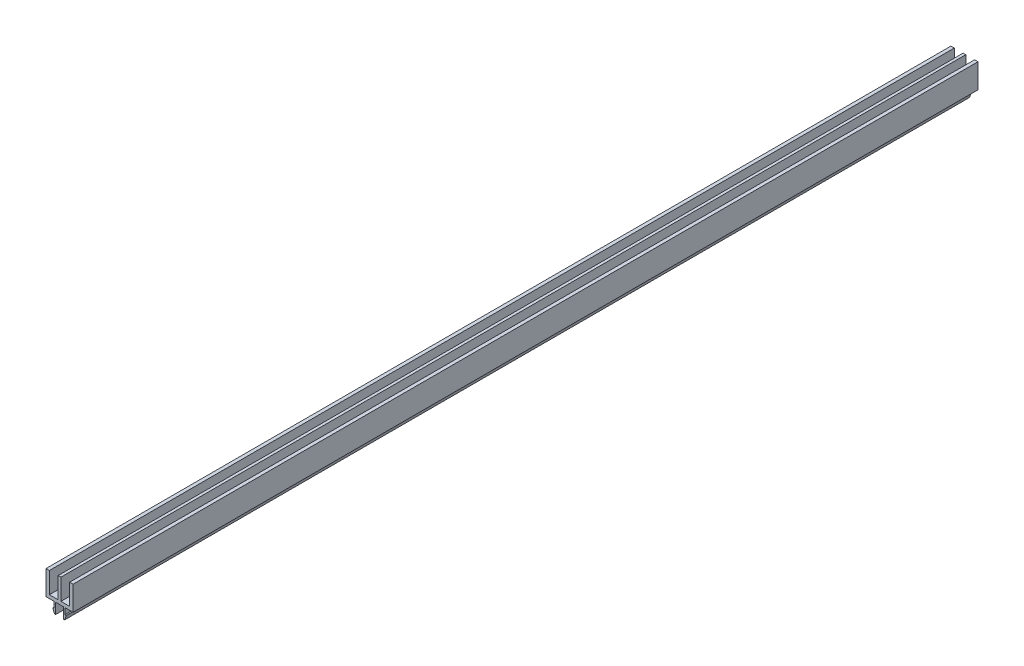
SolidWorks part; units mm, degrees
ref_plane "Plan de face" through (0, 0, 0) normal (0, 0, 1) x (1, 0, 0)
ref_plane "Plan de dessus" through (0, 0, 0) normal (0, 1, 0) x (1, 0, 0)
ref_plane "Plan de droite" through (0, 0, 0) normal (1, 0, 0) x (0, 0, -1)
ref_plane "Plan1" through (0, 0, 50) normal (0, 0, 1) x (1, 0, 0)
sketch "Esquisse1" plane through (0, 0, 50) normal (0, 0, 1) x (1, 0, 0)
  line L0 (-1, 2.5) -> (-7.5, 2.5)
  line L1 (-7.5, 2.5) -> (-7.5, 18)
  line L2 (-7.5, 18) -> (-10, 18)
  line L3 (-10, 18) -> (-10, 0)
  line L4 (-10, 0) -> (-4, 0)
  line L5 (-4, 0) -> (-4, -4.5)
  line L6 (-4, -4.5) -> (-5, -4.5)
  line L7 (-5, -4.5) -> (-3.75, -8)
  line L8 (-3.75, -8) -> (-3, -8)
  line L9 (-3, -8) -> (-3, 0)
  line L10 (-3, 0) -> (3, 0)
  line L11 (3, 0) -> (3, -8)
  line L12 (3, -8) -> (3.75, -8)
  line L13 (3.75, -8) -> (5, -4.5)
  line L14 (5, -4.5) -> (4, -4.5)
  line L15 (4, -4.5) -> (4, 0)
  line L16 (4, 0) -> (10, 0)
  line L17 (10, 0) -> (10, 18)
  line L18 (10, 18) -> (7.5, 18)
  line L19 (7.5, 18) -> (7.5, 2.5)
  line L20 (7.5, 2.5) -> (1, 2.5)
  line L21 (1, 2.5) -> (1, 18)
  line L22 (1, 18) -> (-1, 18)
  line L23 (-1, 18) -> (-1, 2.5)
extrude "Boss.-Extru.1" add sketch "Esquisse1" against normal blind 668
